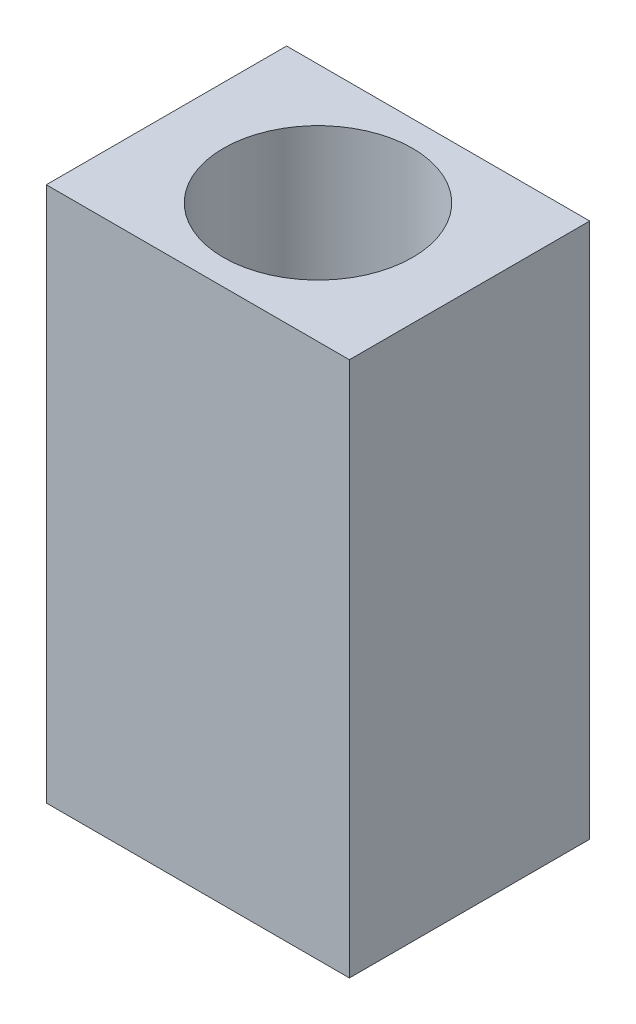
SolidWorks part; units mm, degrees
ref_plane "Alzado" through (0, 0, 0) normal (0, 0, 1) x (1, 0, 0)
ref_plane "Planta" through (0, 0, 0) normal (0, 1, 0) x (1, 0, 0)
ref_plane "Vista lateral" through (0, 0, 0) normal (1, 0, 0) x (0, 0, -1)
sketch "Sketch1" plane through (0, 0, 0) normal (0, 1, 0) x (1, 0, 0)
  line L1 (-4.2457, -3.3661) -> (4.2457, -3.3661)
  line L2 (-4.2457, -3.3661) -> (-4.2457, 3.3661)
  line L3 (-4.2457, 3.3661) -> (4.2457, 3.3661)
  line L4 (4.2457, -3.3661) -> (4.2457, 3.3661)
  line L5 (-4.2457, -3.3661) -> (4.2457, 3.3661) construction
  line L6 (-4.2457, 3.3661) -> (4.2457, -3.3661) construction
  circle A0 centre (0, 0) radius 2.5
  dimension "D1" = 5
extrude "Boss-Extrude1" add sketch "Sketch1" along normal blind 15
sketch "Sketch2" plane through (0, 15, 0) normal (0, 1, 0) x (1, 0, 0)
  point P0 (0, 0)
hole_wizard "Taladro de margen para M51" positions "Sketch2" profile "Sketch3" hole size "M5" standard "ISO" end condition through all
sketch "Sketch3" plane through (0, 15, 0) normal (1, 0, 0) x (0, 0, 1)
  line L0 (0, 0) -> (0, 15)
  line L1 (0, 15) -> (2.65, 15)
  line L2 (2.65, 15) -> (2.65, 0)
  line L5 (2.65, 0) -> (0, 0)
  line L11 (0, -6.35) -> (0, 107.95) construction
  dimension "Diámetro de taladro hasta el siguiente" = 5.3
  dimension "Profundidad de taladro hasta el siguiente" = 15
